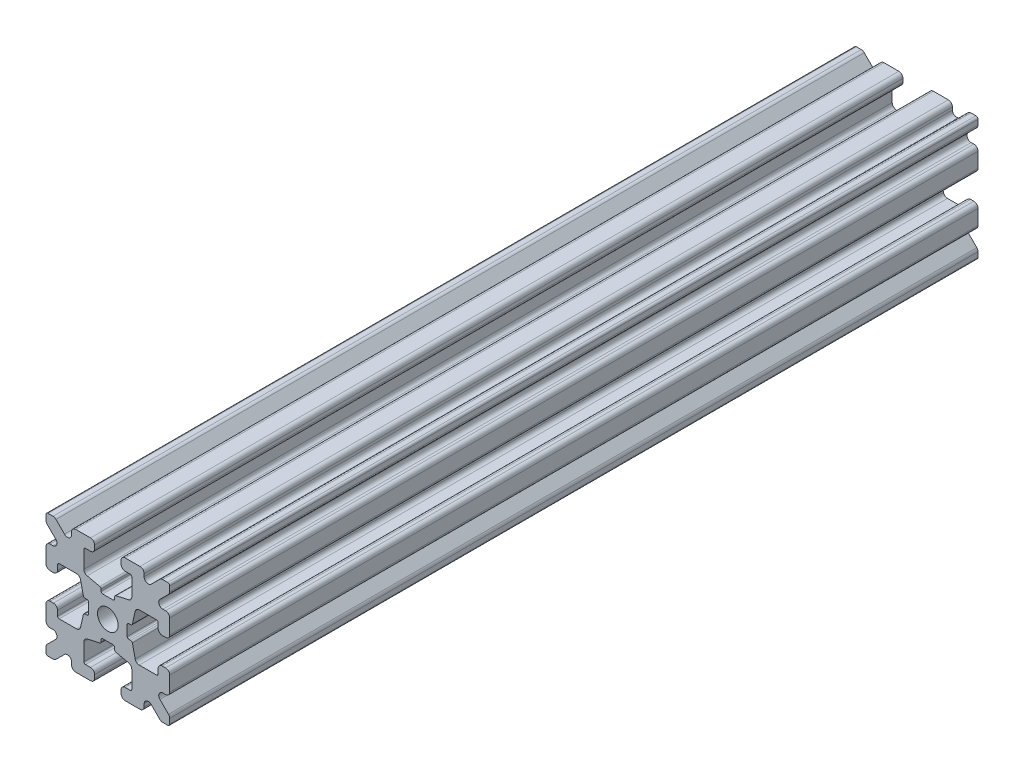
SolidWorks part; units mm, degrees
ref_plane "Front Plane" through (0, 0, 0) normal (0, 0, 1) x (1, 0, 0)
ref_plane "Top Plane" through (0, 0, 0) normal (0, 1, 0) x (1, 0, 0)
ref_plane "Right Plane" through (0, 0, 0) normal (1, 0, 0) x (0, 0, -1)
sketch "Sketch1" plane through (0, 0, 0) normal (0, 0, 1) x (1, 0, 0)
  line L1 (-7.5, -7.5) -> (7.5, -7.5)
  line L2 (-7.5, -7.5) -> (-7.5, 7.5)
  line L3 (-7.5, 7.5) -> (7.5, 7.5)
  line L4 (7.5, -7.5) -> (7.5, 7.5)
  line L5 (-7.5, -7.5) -> (7.5, 7.5) construction
  line L6 (-7.5, 7.5) -> (7.5, -7.5) construction
  circle A0 centre (0, 0) radius 1.25
  point P0 (0, 0)
  dimension "D2" = 2.5
  dimension "D1" = 15
extrude "Boss-Extrude1" add sketch "Sketch1" along normal mid plane 98
fillet "Fillet1" radius 0.25 4 edges at (7.5, -7.5, 0) (-7.5, -7.5, 0) (7.5, 7.5, 0) (-7.5, 7.5, 0)
sketch "Sketch2" plane through (0, 0, 49) normal (0, 0, 1) x (1, 0, 0)
  line L0 (-7.5, 7.25) -> (-7.5, -7.25) construction
  line L1 (-7.5, 1.6) -> (-6.1, 1.6)
  line L2 (-7.5, 1.6) -> (-7.5, -1.6)
  line L3 (-7.5, -1.6) -> (-6.1, -1.6)
  line L4 (-6.1, 1.6) -> (-6.1, 2.9)
  line L5 (0, 0) -> (-12.1036, 0) construction
  line L6 (-6.1, -2.9) -> (-3.4, -2.9)
  line L7 (0, 0) -> (-7.25, 7.25) construction
  line L8 (-6.1, 2.9) -> (-3.4, 2.9)
  line L9 (-3.4, -2.9) -> (-3.4, 2.9)
  line L10 (55, 0) -> (-55, 0) construction
  line L11 (-6.1, -2.9) -> (-6.1, -1.6)
  line L12 (2.9, 6.1) -> (1.6, 6.1)
  line L13 (2.9, 3.4) -> (-2.9, 3.4)
  line L14 (-2.9, 6.1) -> (-2.9, 3.4)
  line L15 (2.9, 6.1) -> (2.9, 3.4)
  line L16 (-1.6, 6.1) -> (-2.9, 6.1)
  line L17 (1.6, 7.5) -> (1.6, 6.1)
  line L18 (-1.6, 7.5) -> (1.6, 7.5)
  line L19 (-1.6, 7.5) -> (-1.6, 6.1)
  line L20 (-1.6, -7.5) -> (-1.6, -6.1)
  line L21 (-1.6, -7.5) -> (1.6, -7.5)
  line L22 (1.6, -7.5) -> (1.6, -6.1)
  line L23 (-1.6, -6.1) -> (-2.9, -6.1)
  line L24 (2.9, -6.1) -> (2.9, -3.4)
  line L25 (-2.9, -6.1) -> (-2.9, -3.4)
  line L26 (2.9, -3.4) -> (-2.9, -3.4)
  line L27 (2.9, -6.1) -> (1.6, -6.1)
  line L28 (6.1, -2.9) -> (6.1, -1.6)
  line L29 (3.4, -2.9) -> (3.4, 2.9)
  line L30 (6.1, 2.9) -> (3.4, 2.9)
  line L31 (6.1, -2.9) -> (3.4, -2.9)
  line L32 (6.1, 1.6) -> (6.1, 2.9)
  line L33 (7.5, -1.6) -> (6.1, -1.6)
  line L34 (7.5, 1.6) -> (7.5, -1.6)
  line L35 (7.5, 1.6) -> (6.1, 1.6)
  dimension "D1" = 3.2
  dimension "D2" = 5.8
  dimension "D3" = 1.4
  dimension "D4" = 2.7
extrude "Cut-Extrude1" cut sketch "Sketch2" against normal through all
sketch "Sketch4" plane through (0, 0, 49) normal (0, 0, 1) x (1, 0, 0)
  line L0 (-3.4, 2.9) -> (-2.75, 0)
  line L1 (55, 0) -> (-55, 0) construction
  line L2 (-2.75, 0) -> (-3.4, -2.9)
  line L3 (-3.4, -2.9) -> (-3.4, 2.9) construction
  line L4 (-3.4, 2.9) -> (-3.4, -2.9)
  line L5 (-2.9, 3.4) -> (0, 2.75)
  line L6 (0, 2.75) -> (2.9, 3.4)
  line L7 (2.9, 3.4) -> (-2.9, 3.4)
  line L8 (3.4, 2.9) -> (2.75, 0)
  line L9 (2.75, 0) -> (3.4, -2.9)
  line L10 (3.4, -2.9) -> (3.4, 2.9)
  line L11 (-2.9, -3.4) -> (0, -2.75)
  line L12 (0, -2.75) -> (2.9, -3.4)
  line L13 (2.9, -3.4) -> (-2.9, -3.4)
  circle A2 centre (0, 0) radius 2.75
  circle A3 centre (0, 0) radius 2.75 construction
  dimension "D1" = 1.5
extrude "Cut-Extrude3" cut sketch "Sketch4" against normal through all
fillet "Fillet3" radius 0.5 16 edges at (-6.1, -1.6, 0) (-7.5, -1.6, 0) (-6.1, 1.6, 0) (-7.5, 1.6, 0) (-1.6, -7.5, 0) (-1.6, -6.1, 0) (1.6, -7.5, 0) (1.6, -6.1, 0) (6.1, -1.6, 0) (7.5, -1.6, 0) (7.5, 1.6, 0) (6.1, 1.6, 0) (1.6, 7.5, 0) (1.6, 6.1, 0) (-1.6, 7.5, 0) (-1.6, 6.1, 0)
fillet "Fillet4" radius 0.5 8 edges at (-3.4, 2.9, 0) (-3.4, -2.9, 0) (2.9, -3.4, 0) (-2.9, -3.4, 0) (3.4, -2.9, 0) (3.4, 2.9, 0) (-2.9, 3.4, 0) (2.9, 3.4, 0)
fillet "Fillet5" radius 3 4 edges at (0, -2.75, 0) (2.75, 0, 0) (-2.75, 0, 0) (0, 2.75, 0)
fillet "Fillet6" radius 0.2 8 edges at (-2.9, -6.1, 0) (2.9, -6.1, 0) (6.1, -2.9, 0) (6.1, 2.9, 0) (2.9, 6.1, 0) (-2.9, 6.1, 0) (-6.1, -2.9, 0) (-6.1, 2.9, 0)
sketch "Sketch5" plane through (0, 0, 49) normal (0, 0, 1) x (1, 0, 0)
  line L0 (0, 0) -> (-7.25, 7.25) construction
  line L1 (-7.5, 6.4393) -> (-5.4607, 4.4)
  line L2 (-6.4393, 7.5) -> (-4.4, 5.4607)
  line L3 (-7.5, 4.4) -> (-5.4607, 4.4)
  line L4 (-3.8003, 2.9) -> (-5.9, 2.9) construction
  line L5 (0, 0) -> (-12.1819, 0) construction
  line L6 (-4.4, 7.5) -> (-4.4, 5.4607)
  line L7 (-2.9, 5.9) -> (-2.9, 3.8003) construction
  line L8 (-7.5, 6.4393) -> (-7.5, 4.4)
  line L9 (-7.5, 7.25) -> (-7.5, 2.1) construction
  line L10 (2.1, -7.5) -> (7.25, -7.5) construction
  line L11 (7.5, -7.25) -> (7.5, -2.1) construction
  line L12 (7.25, 7.5) -> (2.1, 7.5) construction
  line L13 (-2.1, 7.5) -> (-7.25, 7.5) construction
  line L14 (-4.4, 7.5) -> (-6.4393, 7.5)
  line L16 (55, 0) -> (-55, 0) construction
  line L17 (0, 0) -> (0, 10.993) construction
  line L18 (0, -54.6431) -> (0, 54.6431) construction
  line L20 (4.4, 7.5) -> (6.4393, 7.5)
  line L22 (7.5, 6.4393) -> (7.5, 4.4)
  line L23 (4.4, 7.5) -> (4.4, 5.4607)
  line L24 (7.5, 4.4) -> (5.4607, 4.4)
  line L25 (6.4393, 7.5) -> (4.4, 5.4607)
  line L26 (7.5, 6.4393) -> (5.4607, 4.4)
  line L27 (7.5, -6.4393) -> (5.4607, -4.4)
  line L28 (6.4393, -7.5) -> (4.4, -5.4607)
  line L29 (7.5, -4.4) -> (5.4607, -4.4)
  line L30 (4.4, -7.5) -> (4.4, -5.4607)
  line L31 (7.5, -6.4393) -> (7.5, -4.4)
  line L33 (4.4, -7.5) -> (6.4393, -7.5)
  line L36 (-4.4, -7.5) -> (-6.4393, -7.5)
  line L38 (-7.5, -6.4393) -> (-7.5, -4.4)
  line L39 (-4.4, -7.5) -> (-4.4, -5.4607)
  line L40 (-7.5, -4.4) -> (-5.4607, -4.4)
  line L41 (-6.4393, -7.5) -> (-4.4, -5.4607)
  line L42 (-7.5, -6.4393) -> (-5.4607, -4.4)
  dimension "D1" = 1.5
  dimension "D2" = 1.5
  dimension "D3" = 1.5
extrude "Cut-Extrude4" cut sketch "Sketch5" against normal through all
fillet "Fillet8" radius 0.5 24 edges at (-5.4607, 4.4, 0) (-7.5, 4.4, 0) (-5.4607, -4.4, 0) (-7.5, -4.4, 0) (-4.4, -7.5, 0) (-4.4, -5.4607, 0) (4.4, -7.5, 0) (4.4, -5.4607, 0) (5.4607, -4.4, 0) (7.5, -4.4, 0) (7.5, 4.4, 0) (5.4607, 4.4, 0) (4.4, 5.4607, 0) (4.4, 7.5, 0) (-4.4, 5.4607, 0) (-4.4, 7.5, 0) (-6.4393, 7.5, 0) (-7.5, 6.4393, 0) (6.4393, 7.5, 0) (7.5, 6.4393, 0) (6.4393, -7.5, 0) (7.5, -6.4393, 0) (-6.4393, -7.5, 0) (-7.5, -6.4393, 0)
sketch "Sketch6" plane through (0, 0, 49) normal (0, 0, 1) x (1, 0, 0)
  line L0 (0, 0) -> (0, 11.013) construction
  line L1 (0.6561, 2.8971) -> (2.1235, 2.8971) construction
  line L2 (0, -54.6431) -> (0, 54.6431) construction
  line L3 (0, 0) -> (7.25, 7.25) construction
  line L4 (7.5, 0.8255) -> (7.5, -0.8255)
  line L5 (2.3471, 0.8255) -> (7.5, 0.8255)
  line L6 (0, 0) -> (12.4016, 0) construction
  line L7 (0.8255, -7.5) -> (-0.8255, -7.5)
  line L8 (2.3471, -0.8255) -> (2.3471, 0.8255)
  line L9 (0.8255, -2.3471) -> (0.8255, -7.5)
  line L10 (7.5, -0.8255) -> (2.3471, -0.8255)
  line L11 (-7.5, -0.8255) -> (-2.3471, -0.8255)
  line L12 (-2.3471, -0.8255) -> (-2.3471, 0.8255)
  line L13 (-0.8255, -2.3471) -> (0.8255, -2.3471)
  line L14 (-0.8255, 7.5) -> (-0.8255, 2.3471)
  line L15 (-0.8255, 2.3471) -> (0.8255, 2.3471)
  line L16 (-0.8255, -7.5) -> (-0.8255, -2.3471)
  line L17 (0.8255, 2.3471) -> (0.8255, 7.5)
  line L18 (0.8255, 7.5) -> (-0.8255, 7.5)
  line L19 (3.9, 7.5) -> (2.1, 7.5) construction
  line L20 (-2.3471, 0.8255) -> (-7.5, 0.8255)
  line L21 (-7.5, 0.8255) -> (-7.5, -0.8255)
  point P5 (0, -2.5973)
  point P7 (0, 2.5973)
  dimension "D3" = 0.55
  dimension "D1" = 1.651
extrude "Cut-Extrude5" cut sketch "Sketch6" against normal through all
fillet "Fillet10" radius 0.2 16 edges at (-2.935, 0.8255, 0) (-2.935, -0.8255, 0) (2.935, -0.8255, 0) (2.935, 0.8255, 0) (0.8255, 2.935, 0) (-0.8255, 2.935, 0) (-2.3471, 0.8255, 0) (-2.3471, -0.8255, 0) (0.8255, 2.3471, 0) (-0.8255, 2.3471, 0) (2.3471, 0.8255, 0) (2.3471, -0.8255, 0) (0.8255, -2.935, 0) (0.8255, -2.3471, 0) (-0.8255, -2.3471, 0) (-0.8255, -2.935, 0)
